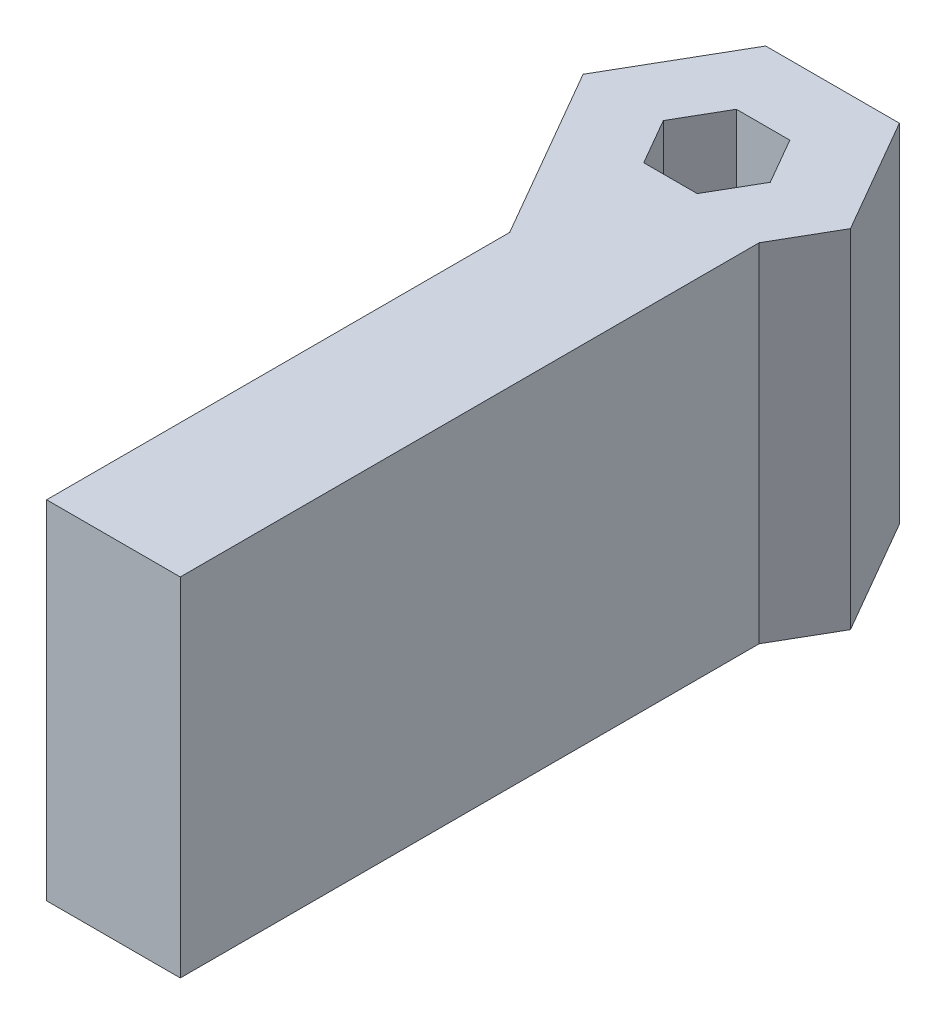
SolidWorks part; units mm, degrees
ref_plane "Front Plane" through (0, 0, 0) normal (0, 0, 1) x (1, 0, 0)
ref_plane "Top Plane" through (0, 0, 0) normal (0, 1, 0) x (1, 0, 0)
ref_plane "Right Plane" through (0, 0, 0) normal (1, 0, 0) x (0, 0, -1)
sketch "Sketch1" plane through (0, 0, 0) normal (0, 1, 0) x (1, 0, 0)
  line L0 (-1.4434, -7.5) -> (-1.4434, -27.5)
  line L1 (2.3094, 0) -> (1.1547, 2)
  line L2 (1.1547, 2) -> (-1.1547, 2)
  line L3 (-1.1547, 2) -> (-2.3094, 0)
  line L4 (-2.3094, 0) -> (-1.1547, -2)
  line L5 (-1.1547, -2) -> (1.1547, -2)
  line L6 (1.1547, -2) -> (2.3094, 0)
  line L7 (5.7735, 0) -> (2.8868, 5)
  line L8 (2.8868, 5) -> (-2.8868, 5)
  line L9 (-2.8868, 5) -> (-5.7735, 0)
  line L10 (-5.7735, 0) -> (-1.4434, -7.5)
  line L12 (4.3301, -2.5) -> (5.7735, 0)
  line L13 (-1.4434, -27.5) -> (4.3301, -27.5)
  line L14 (4.3301, -27.5) -> (4.3301, -2.5)
  line L16 (0, -5) -> (2.8868, -5) [skipped]
  circle A0 centre (0, 0) radius 2 construction
  circle A1 centre (0, 0) radius 5 construction
  dimension "D1" = 4
  dimension "D2" = 3
  dimension "D3" = 25
  dimension "D4" = 5.7735
  dimension "D5" = 20
extrude "Boss-Extrude1" add sketch "Sketch1" along normal blind 15
